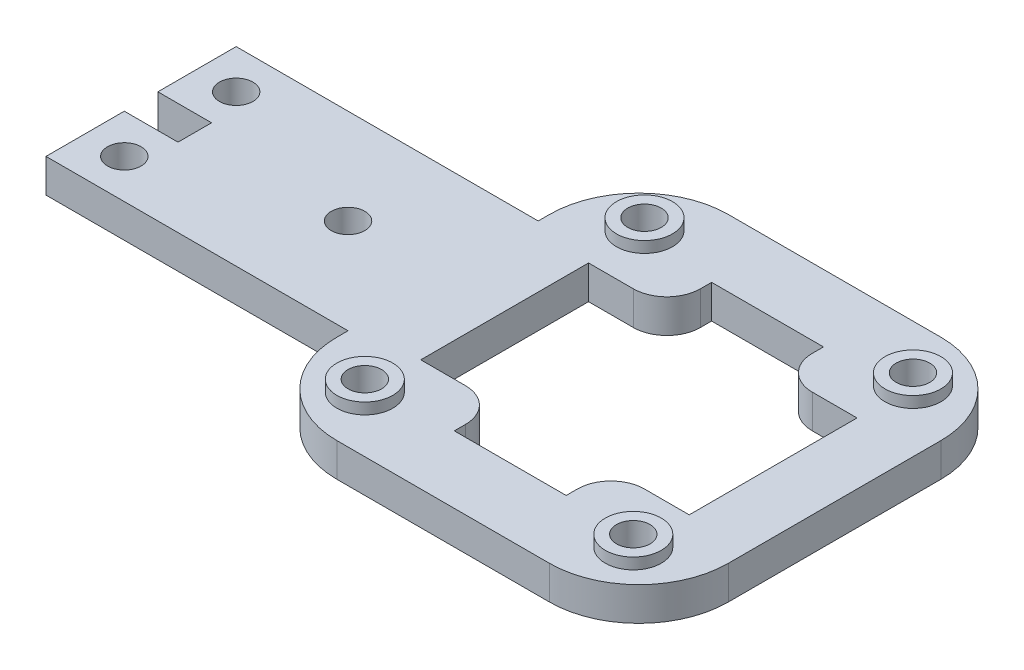
SolidWorks part; units mm, degrees
ref_plane "前视基准面" through (0, 0, 0) normal (0, 0, 1) x (1, 0, 0)
ref_plane "上视基准面" through (0, 0, 0) normal (0, 1, 0) x (1, 0, 0)
ref_plane "右视基准面" through (0, 0, 0) normal (1, 0, 0) x (0, 0, -1)
other "Configuration Table"
sketch "草图1" plane through (0, 0, 0) normal (0, 1, 0) x (1, 0, 0)
  line L0 (-4, 0) -> (-2.5, 0)
  line L1 (-17.5, 5) -> (-15.4412, 5) construction
  line L2 (-17.5, 5) -> (-17.5, -5) construction
  line L3 (-17.5, -5) -> (-15.4412, -5) construction
  line L4 (17.5, 5) -> (17.5, -5) construction
  line L5 (-17.5, 5) -> (-15.6579, 4.4737) construction
  line L6 (-17.5, -5) -> (-15.6579, -4.4737) construction
  line L7 (5.5, 12.5) -> (29.5, 12.5) construction
  line L8 (5.5, 12.5) -> (5.5, -12.5) construction
  line L9 (5.5, -12.5) -> (29.5, -12.5) construction
  line L10 (29.5, 12.5) -> (29.5, -12.5) construction
  line L11 (5.5, 12.5) -> (29.5, -12.5) construction
  line L12 (5.5, -12.5) -> (29.5, 12.5) construction
  line L13 (5.5, 7.5) -> (29.5, 7.5)
  line L14 (5.5, 7.5) -> (5.5, -7.5)
  line L15 (5.5, -7.5) -> (29.5, -7.5)
  line L16 (29.5, 7.5) -> (29.5, -7.5)
  line L17 (5.5, 7.5) -> (29.5, -7.5) construction
  line L18 (5.5, -7.5) -> (29.5, 7.5) construction
  line L19 (0, 17.5) -> (35, 17.5)
  line L20 (0, 17.5) -> (0, 8.5)
  line L21 (0, -17.5) -> (35, -17.5)
  line L22 (35, 17.5) -> (35, -17.5)
  line L23 (0, 17.5) -> (35, -17.5) construction
  line L24 (0, -17.5) -> (35, 17.5) construction
  line L25 (-14, 8.5) -> (0, 8.5)
  line L26 (-21, 8.5) -> (-14, 8.5)
  line L27 (-21, 8.5) -> (-21, -8.5)
  line L28 (-21, -8.5) -> (-14, -8.5)
  line L30 (-21, 8.5) -> (-14, -8.5) construction
  line L31 (-21, -8.5) -> (-14, 8.5) construction
  line L32 (-14, -8.5) -> (0, -8.5)
  line L33 (0, -8.5) -> (0, -17.5)
  line L34 (5.5, -1.5714) -> (17.5, -5) construction
  line L35 (5.5, 1.5714) -> (17.5, 5) construction
  line L36 (5.5, 5) -> (17.5, 5) construction
  line L37 (5.5, -5) -> (17.5, -5) construction
  line L38 (-3.5935, 1.0267) -> (-1.0291, 0.294) construction
  line L39 (-3.5935, -1.0267) -> (-1.0291, -0.294) construction
  circle A0 centre (-17.5, 5) radius 1.5
  circle A1 centre (-17.5, -5) radius 1.5
  circle A2 centre (5.5, 12.5) radius 1.5
  circle A3 centre (29.5, 12.5) radius 1.5
  circle A4 centre (5.5, -12.5) radius 1.5
  circle A5 centre (29.5, -12.5) radius 1.5
  circle A6 centre (-2.5, 0) radius 1.5
  point P0 (0, 0)
  point P8 (17.5, 0)
  point P17 (17.5, 0)
  point P22 (17.5, 0)
  dimension "D2" = 3
  dimension "D3" = 3
  dimension "D7" = 3
  dimension "D8" = 3
  dimension "D9" = 3
  dimension "D10" = 3
  dimension "D14" = 3
  dimension "D1" = 10
  dimension "D4" = 35
  dimension "D5" = 25
  dimension "D6" = 24
  dimension "D11" = 15
  dimension "D12" = 24
  dimension "D15" = 7
  dimension "D16" = 17
  dimension "D17" = 35
  dimension "D18" = 35
extrude "凸台-拉伸1" add sketch "草图1" along normal blind 3 contours L32 L33 L21 L22 L19 L20 L25 L26 L27 L28 A6 A5 A4 A3 A2 A1 A0 L13 L16 L15 L14
sketch "草图2" plane through (0, 3, 0) normal (0, 1, 0) x (1, 0, 0)
  circle A0 centre (5.5, 12.5) radius 1.5
  circle A1 centre (29.5, 12.5) radius 1.5
  circle A2 centre (5.5, -12.5) radius 1.5
  circle A3 centre (29.5, -12.5) radius 1.5
  circle A4 centre (5.5, 12.5) radius 2.5
  circle A5 centre (29.5, 12.5) radius 2.5
  circle A6 centre (29.5, -12.5) radius 2.5
  circle A7 centre (5.5, -12.5) radius 2.5
  dimension "D1" = 5
  dimension "D2" = 5
  dimension "D3" = 5
  dimension "D4" = 5
extrude "凸台-拉伸2" add sketch "草图2" along normal blind 1
sketch "草图3" plane through (0, 3, 0) normal (0, 1, 0) x (1, 0, 0)
  line L0 (-21, 0) -> (-17.5, 0) construction
  line L1 (-21, 8.5) -> (-21, -8.5) construction
  line L3 (-14, 1.5) -> (-21, 1.5)
  line L4 (-14, 1.5) -> (-14, -1.5)
  line L5 (-14, -1.5) -> (-21, -1.5)
  line L6 (-21, 1.5) -> (-21, -1.5)
  line L7 (-14, 1.5) -> (-21, -1.5) construction
  line L8 (-14, -1.5) -> (-21, 1.5) construction
  dimension "D1" = 3.5
  dimension "D2" = 3
extrude "切除-拉伸1" cut sketch "草图3" against normal up to next
fillet "圆角1" radius 8 4 edges at (0, 1.5, -17.5) (0, 1.5, 17.5) (35, 1.5, 17.5) (35, 1.5, -17.5)
sketch "草图4" plane through (0, 3, 0) normal (0, 1, 0) x (1, 0, 0)
  line L0 (-21, 8.5) -> (-27, 8.5)
  line L1 (-27, 8.5) -> (-27, 1.5)
  line L2 (-27, -8.5) -> (-21, -8.5)
  line L3 (-21, -8.5) -> (-21, -1.5)
  line L4 (-21, -1.5) -> (-14, -1.5)
  line L5 (-14, -1.5) -> (-14, 1.5)
  line L6 (-14, 1.5) -> (-21, 1.5)
  line L7 (-21, 1.5) -> (-21, 8.5)
  line L8 (-22.2, 1.5) -> (-27, 1.5)
  line L9 (-22.2, -1.5) -> (-27, -1.5)
  line L10 (-22.2, 1.5) -> (-22.2, -1.5)
  line L11 (-27, -1.5) -> (-27, -8.5)
  dimension "D1" = 6
  dimension "D2" = 1.2
extrude "凸台-拉伸3" add sketch "草图4" against normal up to surface (3 mm away) up to face at (-2.5, 0, 1.5)
sketch "草图5" plane through (0, 3, 0) normal (0, 1, 0) x (1, 0, 0)
  line L0 (-17.5, 5) -> (-23.5, 5) construction
  line L1 (-17.5, -5) -> (-23.5, -5) construction
  line L2 (-2.5, 0) -> (-8.5, 0) construction
  circle A0 centre (-23.5, 5) radius 1.5
  circle A1 centre (-23.5, -5) radius 1.5
  circle A2 centre (-8.5, 0) radius 1.5
  dimension "D2" = 3
  dimension "D4" = 3
  dimension "D6" = 3
  dimension "D1" = 6
  dimension "D3" = 6
  dimension "D5" = 6
extrude "切除-拉伸2" cut sketch "草图5" against normal up to next
sketch "草图6" plane through (0, 3, 0) normal (0, 1, 0) x (1, 0, 0)
  circle A0 centre (-17.5, 5) radius 1.5
  circle A1 centre (-2.5, 0) radius 1.5
  circle A2 centre (-17.5, -5) radius 1.5
extrude "凸台-拉伸4" add sketch "草图6" against normal up to surface (3 mm away) up to face at (-23.5, 0, -3.5)
sketch "草图7" plane through (0, 3, 0) normal (0, 1, 0) x (1, 0, 0)
  line L0 (17.5, 7.5) -> (17.5, 11.5) construction
  line L1 (5.5, 7.5) -> (29.5, 7.5) construction
  line L2 (17.5, 11.5) -> (12.5, 11.5)
  line L3 (12.5, 11.5) -> (12.5, 7.5)
  line L4 (12.5, 7.5) -> (22.5, 7.5)
  line L5 (22.5, 7.5) -> (22.5, 11.5)
  line L6 (22.5, 11.5) -> (17.5, 11.5)
  line L7 (-2.2, 0) -> (2.2, 0) construction
  line L8 (22.5, -11.5) -> (17.5, -11.5)
  line L9 (22.5, -7.5) -> (22.5, -11.5)
  line L10 (12.5, -7.5) -> (22.5, -7.5)
  line L11 (12.5, -11.5) -> (12.5, -7.5)
  line L12 (17.5, -11.5) -> (12.5, -11.5)
  dimension "D1" = 4
  dimension "D2" = 5
  dimension "D3" = 10
extrude "切除-拉伸3" cut sketch "草图7" against normal through all
fillet "圆角2" radius 3 4 edges at (22.5, 1.5, -7.5) (12.5, 1.5, 7.5) (22.5, 1.5, 7.5) (12.5, 1.5, -7.5)
